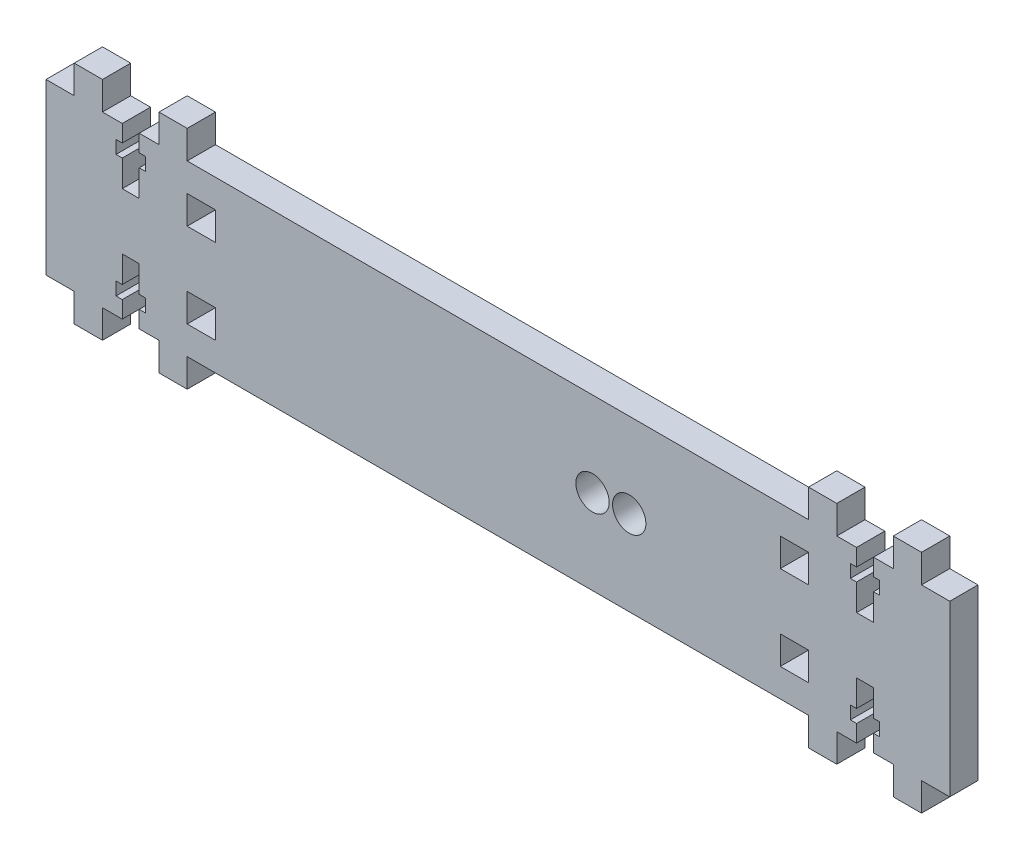
SolidWorks part; units mm, degrees
ref_plane "Front Plane" through (0, 0, 0) normal (0, 0, 1) x (1, 0, 0)
ref_plane "Top Plane" through (0, 0, 0) normal (0, 1, 0) x (1, 0, 0)
ref_plane "Right Plane" through (0, 0, 0) normal (1, 0, 0) x (0, 0, -1)
sketch "Sketch2" plane through (0, 0, 0) normal (0, 0, 1) x (1, 0, 0)
  line L0 (0, 0) -> (105.2075, 0) construction
  line L1 (0, 0) -> (0, 49.6369) construction
  line L2 (-80, 15) -> (80, 15) construction
  line L3 (80, 15) -> (80, -15) construction
  line L4 (80, -15) -> (-80, -15) construction
  line L5 (-80, -15) -> (-80, 15) construction
  line L6 (65, 15) -> (65, 3.7792) construction
  line L7 (66.5, 15) -> (70, 15)
  line L8 (70, 20) -> (75, 20)
  line L9 (75, 20) -> (75, 15)
  line L10 (70, 20) -> (70, 15)
  line L11 (63.5, 15) -> (60, 15)
  line L12 (60, 15) -> (60, 20)
  line L13 (60, 20) -> (55, 20)
  line L14 (55, 20) -> (55, 15)
  line L15 (66.5, 15) -> (63.5, 15) construction
  line L16 (63.5, 15) -> (63.5, 12)
  line L17 (63.5, 9.7) -> (62.4, 9.7)
  line L18 (67.6, 12) -> (67.6, 9.7)
  line L19 (62.4, 12) -> (63.5, 12)
  line L20 (63.5, 9.7) -> (63.5, 5)
  line L21 (63.5, 5) -> (66.5, 5)
  line L22 (66.5, 5) -> (66.5, 9.7)
  line L23 (66.5, 12) -> (67.6, 12)
  line L24 (62.4, 9.7) -> (62.4, 12)
  line L25 (67.6, 9.7) -> (66.5, 9.7)
  line L26 (66.5, 12) -> (66.5, 15)
  line L27 (65, 5) -> (65, 15) construction
  line L28 (-55, 20) -> (-55, 15)
  line L29 (-60, 20) -> (-55, 20)
  line L30 (-60, 15) -> (-60, 20)
  line L31 (-63.5, 15) -> (-60, 15)
  line L32 (-63.5, 15) -> (-63.5, 12)
  line L33 (-62.4, 12) -> (-63.5, 12)
  line L34 (-62.4, 9.7) -> (-62.4, 12)
  line L35 (-63.5, 9.7) -> (-62.4, 9.7)
  line L36 (-63.5, 9.7) -> (-63.5, 5)
  line L37 (-63.5, 5) -> (-66.5, 5)
  line L38 (-66.5, 5) -> (-66.5, 9.7)
  line L39 (-67.6, 9.7) -> (-66.5, 9.7)
  line L40 (-67.6, 12) -> (-67.6, 9.7)
  line L41 (-66.5, 12) -> (-67.6, 12)
  line L42 (-66.5, 12) -> (-66.5, 15)
  line L43 (-66.5, 15) -> (-70, 15)
  line L44 (-70, 20) -> (-70, 15)
  line L45 (-70, 20) -> (-75, 20)
  line L46 (-75, 20) -> (-75, 15)
  line L47 (55, -20) -> (55, -15)
  line L48 (60, -20) -> (55, -20)
  line L49 (60, -15) -> (60, -20)
  line L50 (63.5, -15) -> (60, -15)
  line L51 (63.5, -15) -> (63.5, -12)
  line L52 (62.4, -12) -> (63.5, -12)
  line L53 (62.4, -9.7) -> (62.4, -12)
  line L54 (63.5, -9.7) -> (62.4, -9.7)
  line L55 (63.5, -9.7) -> (63.5, -5)
  line L56 (63.5, -5) -> (66.5, -5)
  line L57 (66.5, -5) -> (66.5, -9.7)
  line L58 (67.6, -9.7) -> (66.5, -9.7)
  line L59 (67.6, -12) -> (67.6, -9.7)
  line L60 (66.5, -12) -> (67.6, -12)
  line L61 (66.5, -12) -> (66.5, -15)
  line L62 (66.5, -15) -> (70, -15)
  line L63 (70, -20) -> (70, -15)
  line L64 (70, -20) -> (75, -20)
  line L65 (75, -20) -> (75, -15)
  line L66 (-75, -20) -> (-75, -15)
  line L67 (-70, -20) -> (-75, -20)
  line L68 (-70, -20) -> (-70, -15)
  line L69 (-66.5, -15) -> (-70, -15)
  line L70 (-66.5, -12) -> (-66.5, -15)
  line L71 (-66.5, -12) -> (-67.6, -12)
  line L72 (-67.6, -12) -> (-67.6, -9.7)
  line L73 (-67.6, -9.7) -> (-66.5, -9.7)
  line L74 (-66.5, -5) -> (-66.5, -9.7)
  line L75 (-63.5, -5) -> (-66.5, -5)
  line L76 (-63.5, -9.7) -> (-63.5, -5)
  line L77 (-63.5, -9.7) -> (-62.4, -9.7)
  line L78 (-62.4, -9.7) -> (-62.4, -12)
  line L79 (-62.4, -12) -> (-63.5, -12)
  line L80 (-63.5, -15) -> (-63.5, -12)
  line L81 (-63.5, -15) -> (-60, -15)
  line L82 (-60, -15) -> (-60, -20)
  line L83 (-60, -20) -> (-55, -20)
  line L84 (-55, -20) -> (-55, -15)
  line L85 (-55, 15) -> (55, 15)
  line L86 (75, 15) -> (80, 15)
  line L87 (80, 15) -> (80, -15)
  line L88 (80, -15) -> (75, -15)
  line L89 (55, -15) -> (-55, -15)
  line L90 (-75, -15) -> (-80, -15)
  line L91 (-80, -15) -> (-80, 15)
  line L92 (-80, 15) -> (-75, 15)
  line L93 (52.5, 5) -> (52.5, -5) construction
  line L94 (55, 5) -> (55, 10)
  line L95 (55, 5) -> (50, 5)
  line L96 (50, 5) -> (50, 10)
  line L97 (55, 10) -> (50, 10)
  line L98 (55, -5) -> (55, -10)
  line L99 (55, -5) -> (50, -5)
  line L100 (50, -5) -> (50, -10)
  line L101 (55, -10) -> (50, -10)
  line L102 (52.5, 0) -> (59.4724, 0) construction
  line L103 (-52.5, 5) -> (-52.5, -5) construction
  line L104 (-55, 5) -> (-55, 10)
  line L105 (-55, 5) -> (-50, 5)
  line L106 (-50, 5) -> (-50, 10)
  line L107 (-55, 10) -> (-50, 10)
  line L108 (-55, -5) -> (-55, -10)
  line L109 (-55, -5) -> (-50, -5)
  line L110 (-50, -5) -> (-50, -10)
  line L111 (-55, -10) -> (-50, -10)
  line L112 (-52.5, 0) -> (-59.4724, 0) construction
  line L113 (16.75, 0) -> (23.25, 0) construction
  line L114 (20, 0) -> (20, 8.1025) construction
  circle A0 centre (23.25, 0) radius 2.95
  circle A1 centre (16.75, 0) radius 2.95
  circle A3 centre (52.5, 0) radius 1.5 construction
  circle A4 centre (-52.5, 0) radius 1.5 construction
  point P124 (0, 0)
  dimension "D13" = 5.9
  dimension "D17" = 3
  dimension "D21" = 3
  dimension "D1" = 55
  dimension "D2" = 10
  dimension "D3" = 5
  dimension "D4" = 5
  dimension "D5" = 5.2
  dimension "D6" = 3
  dimension "D7" = 2.3
  dimension "D8" = 3
  dimension "D9" = 10
  dimension "D10" = 30
  dimension "D11" = 5
  dimension "D12" = 50
  dimension "D14" = 6.5
  dimension "D15" = 20
  dimension "D16" = 5
  dimension "D18" = 5
  dimension "D19" = 10
  dimension "D20" = 5
  dimension "D22" = 5
  dimension "D23" = 10
extrude "Boss-Extrude1" add sketch "Sketch2" along normal blind 5
